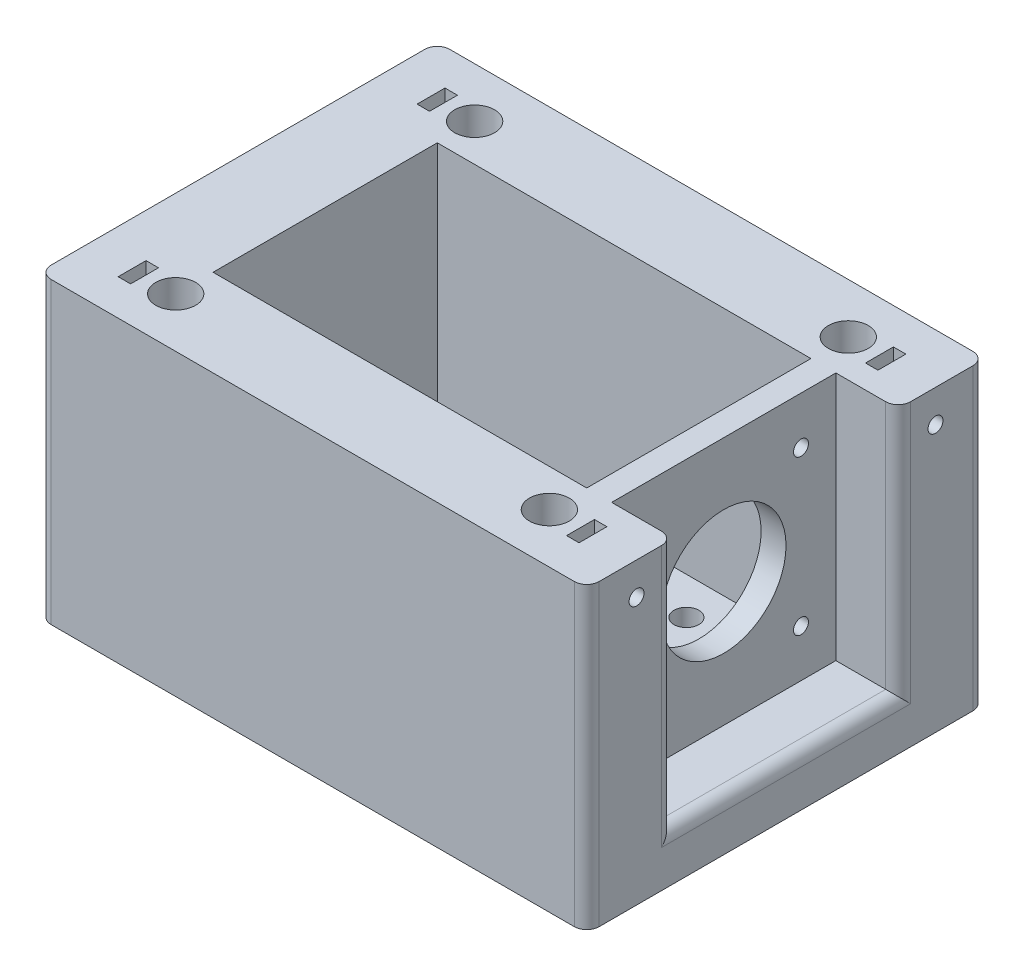
SolidWorks part; units mm, degrees
ref_plane "Front Plane" through (0, 0, 0) normal (0, 0, 1) x (1, 0, 0)
ref_plane "Top Plane" through (0, 0, 0) normal (0, 1, 0) x (1, 0, 0)
ref_plane "Right Plane" through (0, 0, 0) normal (1, 0, 0) x (0, 0, -1)
sketch "Sketch1" plane through (0, 0, 0) normal (0, 1, 0) x (1, 0, 0)
  line L1 (-55, 40) -> (55, 40)
  line L2 (-55, 40) -> (-55, -40)
  line L3 (-55, -40) -> (55, -40)
  line L4 (55, 40) -> (55, -40)
  line L5 (-55, 40) -> (55, -40) construction
  line L6 (-55, -40) -> (55, 40) construction
  point P0 (0, 0)
  dimension "D1" = 80
  dimension "D2" = 110
extrude "Boss-Extrude1" add sketch "Sketch1" along normal blind 60
sketch "Sketch2" plane through (0, 60, 0) normal (0, 1, 0) x (1, 0, 0)
  line L1 (-37.5, 22.5) -> (37.5, 22.5)
  line L2 (-37.5, 22.5) -> (-37.5, -22.5)
  line L3 (-37.5, -22.5) -> (37.5, -22.5)
  line L4 (37.5, 22.5) -> (37.5, -22.5)
  line L5 (-37.5, 22.5) -> (37.5, -22.5) construction
  line L6 (-37.5, -22.5) -> (37.5, 22.5) construction
  line L7 (-37.5, 30) -> (37.5, 30)
  line L8 (-37.5, 30) -> (-37.5, -30)
  line L9 (-37.5, -30) -> (37.5, -30)
  line L10 (37.5, 30) -> (37.5, -30)
  line L11 (-37.5, 30) -> (37.5, -30) construction
  line L12 (-37.5, -30) -> (37.5, 30) construction
  line L17 (55, -40) -> (55, 40) construction
  line L18 (42.5, 22.5) -> (55, 22.5)
  line L19 (42.5, 22.5) -> (42.5, -22.5)
  line L20 (42.5, -22.5) -> (55, -22.5)
  line L21 (55, 22.5) -> (55, -22.5)
  circle A0 centre (-37.5, 30) radius 4
  circle A1 centre (37.5, 30) radius 4
  circle A2 centre (37.5, -30) radius 4
  circle A3 centre (-37.5, -30) radius 4
  point P0 (0, 0)
  point P5 (0, 0)
  line M4 (55, -40) -> (55, 40)
  dimension "D5" = 8
  dimension "D1" = 45
  dimension "D2" = 75
  dimension "D3" = 60
  dimension "D4" = 75
  dimension "D8" = 5
  dimension "D9" = 45
  dimension "D10" = 0
  dimension "D11" = 0
  dimension "D6" = 2
  dimension "D7" = 2
extrude "Cut-Extrude2" cut sketch "Sketch2" against normal blind 50 contours L4 L1 L2 L3 | L7 A0 L8 | L8 A0 L7 | L10 A1 L7 | L7 A1 L10 | L8 A3 L9 | L9 A3 L8 | L9 A2 L10 | L10 A2 L9 | L19 L20 L18 M4
sketch "Sketch4" plane through (0, 60, 0) normal (0, 1, 0) x (1, 0, 0)
  line L1 (-45, 30) -> (45, 30)
  line L2 (-45, 30) -> (-45, -30)
  line L3 (-45, -30) -> (45, -30)
  line L4 (45, 30) -> (45, -30)
  line L5 (-45, 30) -> (45, -30) construction
  line L6 (-45, -30) -> (45, 30) construction
  line L7 (-46.25, 32.8) -> (-43.75, 32.8)
  line L8 (-46.25, 32.8) -> (-46.25, 27.2)
  line L9 (-46.25, 27.2) -> (-43.75, 27.2)
  line L10 (-43.75, 32.8) -> (-43.75, 27.2)
  line L11 (-46.25, 32.8) -> (-43.75, 27.2) construction
  line L12 (-46.25, 27.2) -> (-43.75, 32.8) construction
  line L20 (-46.25, -27.2) -> (-46.25, -32.8)
  line L21 (-46.25, -27.2) -> (-43.75, -27.2)
  line L22 (-43.75, -27.2) -> (-43.75, -32.8)
  line L23 (-46.25, -32.8) -> (-43.75, -32.8)
  line L24 (54.75, 32.8) -> (54.75, 27.2) [skipped]
  line L25 (54.75, 32.8) -> (57.25, 32.8) [skipped]
  line L26 (57.25, 32.8) -> (57.25, 27.2) [skipped]
  line L27 (54.75, 27.2) -> (57.25, 27.2) [skipped]
  line L28 (54.75, -27.2) -> (54.75, -32.8) [skipped]
  line L29 (54.75, -27.2) -> (57.25, -27.2) [skipped]
  line L30 (57.25, -27.2) -> (57.25, -32.8) [skipped]
  line L31 (54.75, -32.8) -> (57.25, -32.8) [skipped]
  line L32 (43.75, 32.8) -> (46.25, 32.8)
  line L33 (43.75, 32.8) -> (43.75, 27.2)
  line L34 (46.25, 32.8) -> (46.25, 27.2)
  line L35 (43.75, 27.2) -> (46.25, 27.2)
  line L36 (43.75, -27.2) -> (46.25, -27.2)
  line L37 (43.75, -27.2) -> (43.75, -32.8)
  line L38 (46.25, -27.2) -> (46.25, -32.8)
  line L39 (43.75, -32.8) -> (46.25, -32.8)
  point P0 (0, 0)
  point P5 (-45, 30)
  dimension "D1" = 2
  dimension "D2" = 5.6
  dimension "105" = 90
  dimension "D3" = 2.5
  dimension "D4" = 2
  dimension "D5" = 2
extrude "Cut-Extrude3" cut sketch "Sketch4" against normal blind 10 contours L10 L7 L8 L9 L2 L1 | L10 L1 L2 L9 | L20 L23 L22 L3 L2 L21 | L22 L21 L2 L3 | L36 L37 L3 L4 | L37 L39 L38 L36 L4 L3 | L4 L35 L34 L32 L33 L1 | L33 L35 L4 L1
sketch "Sketch5" plane through (55, 0, 0) normal (1, 0, 0) x (0, 0, -1)
  line L0 (-40, 60) -> (-22.5, 60) construction
  circle A0 centre (-30, 53.5) radius 1.5
  circle A1 centre (30, 53.5) radius 1.5
  dimension "D1" = 3
  dimension "D2" = 3
  dimension "D3" = 60
  dimension "D4" = 6.5
  dimension "D5" = 30
extrude "Cut-Extrude4" cut sketch "Sketch5" against normal blind 117
sketch "Sketch6" plane through (42.5, 0, 0) normal (1, 0, 0) x (0, 0, -1)
  line L1 (-15.5, 50.5) -> (15.5, 50.5)
  line L2 (-15.5, 50.5) -> (-15.5, 19.5)
  line L3 (-15.5, 19.5) -> (15.5, 19.5)
  line L4 (15.5, 50.5) -> (15.5, 19.5)
  line L5 (-15.5, 50.5) -> (15.5, 19.5) construction
  line L6 (-15.5, 19.5) -> (15.5, 50.5) construction
  line L7 (-22.5, 10) -> (22.5, 10) construction
  circle A0 centre (0, 35) radius 12.5
  circle A1 centre (-15.5, 50.5) radius 1.5
  circle A2 centre (15.5, 50.5) radius 1.5
  circle A3 centre (15.5, 19.5) radius 1.5
  circle A4 centre (-15.5, 19.5) radius 1.5
  point P0 (0, 35)
  point P15 (31, 35)
  point P18 (31, 4)
  point P21 (0, 4)
  dimension "D4" = 25
  dimension "D5" = 3
  dimension "D1" = 31
  dimension "D2" = 31
  dimension "D3" = 9.5
  dimension "D6" = 2
  dimension "D7" = 2
extrude "Cut-Extrude5" cut sketch "Sketch6" against normal blind 5 contours A0 | L1 A1 L2 | L2 A1 L1 | L1 A2 L4 | L4 A2 L1 | L3 A3 L4 | L4 A3 L3 | L3 A4 L2 | L2 A4 L3
fillet "Fillet1" radius 2.5 7 edges at (-55, 30, 40) (-55, 30, -40) (55, 30, -40) (55, 30, 40) (55, 35, -22.5) (55, 10, 0) (55, 35, 22.5)
sketch "Sketch7" plane through (0, 10, 0) normal (0, 1, 0) x (1, 0, 0)
  line L1 (-20, 15) -> (20, 15) construction
  line L2 (-20, 15) -> (-20, -15) construction
  line L3 (-20, -15) -> (20, -15) construction
  line L4 (20, 15) -> (20, -15) construction
  line L5 (-20, 15) -> (20, -15) construction
  line L6 (-20, -15) -> (20, 15) construction
  circle A0 centre (-20, 15) radius 2.5
  circle A1 centre (20, 15) radius 2.5
  circle A2 centre (-20, -15) radius 2.5
  circle A3 centre (20, -15) radius 2.5
  point P0 (0, 0)
  dimension "D3" = 5
  dimension "D1" = 30
  dimension "D2" = 40
extrude "Cut-Extrude6" cut sketch "Sketch7" against normal blind 10
